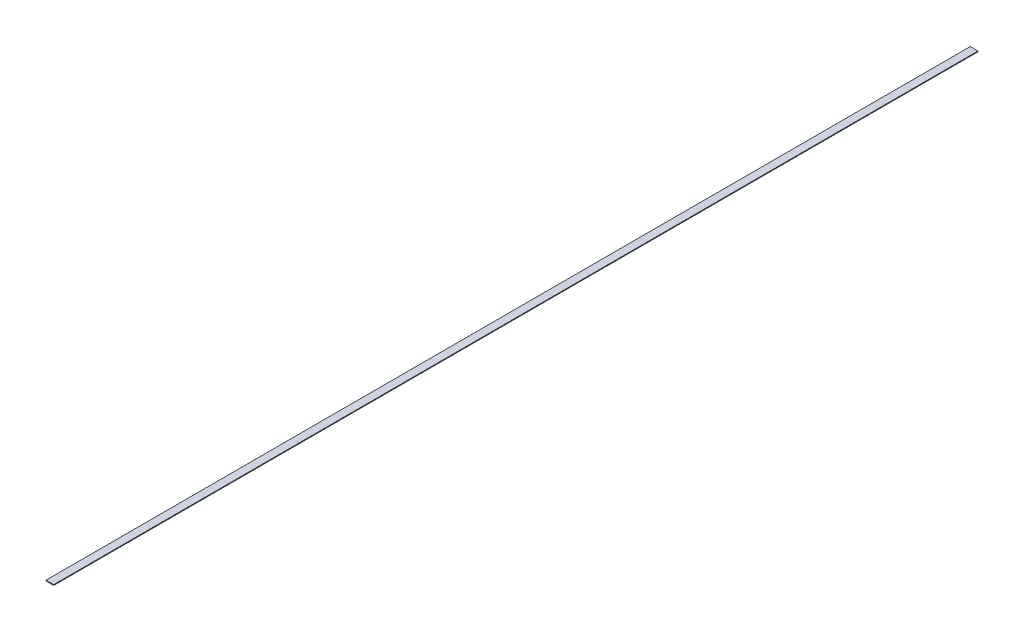
SolidWorks part; units mm, degrees
ref_plane "Front Plane" through (0, 0, 0) normal (0, 0, 1) x (1, 0, 0)
ref_plane "Top Plane" through (0, 0, 0) normal (0, 1, 0) x (1, 0, 0)
ref_plane "Right Plane" through (0, 0, 0) normal (1, 0, 0) x (0, 0, -1)
sketch "Sketch1" plane through (0, 0, 0) normal (0, 0, 1) x (1, 0, 0)
  line L0 (0, 1.1906) -> (0, -1.1906) construction
  line L1 (-12.7, 0) -> (12.7, 0) construction
  point P0 (12.7, 1.1906)
  point P6 (0, 0)
  point P9 (12.7, -1.1906)
  point P10 (-12.7, 1.1906)
  dimension "Width" = 25.4
  dimension "Thickness" = 2.3813
sketch "Sketch2" plane through (0, 0, 0) normal (1, 0, 0) x (0, 0, -1)
  line L0 (1524, 0) -> (-1524, 0)
  line L1 (0, 1.1906) -> (0, -1.1906) construction
  line L2 (0, 1.1906) -> (0, -1.1906) construction
  point P0 (-1524, 1.1906)
  point P4 (0, 0)
  point P11 (1524, 1.1906)
  dimension "Length" = 3048
sketch "Sketch3" plane through (0, 0, 0) normal (0, 0, 1) x (1, 0, 0)
  line L1 (12.7, 1.1906) -> (-12.7, 1.1906)
  line L2 (12.7, 1.1906) -> (12.7, -1.1906)
  line L3 (12.7, -1.1906) -> (-12.7, -1.1906)
  line L4 (-12.7, 1.1906) -> (-12.7, -1.1906)
  line L5 (12.7, 1.1906) -> (-12.7, -1.1906) construction
  line L6 (12.7, -1.1906) -> (-12.7, 1.1906) construction
  point P0 (0, 0)
extrude "Boss-Extrude1" add sketch "Sketch3" along normal up to vertex (1524 mm away) and the other way up to vertex (1524 mm away) up to point (0, 0, 1524) other way up to point (0, 0, -1524)
